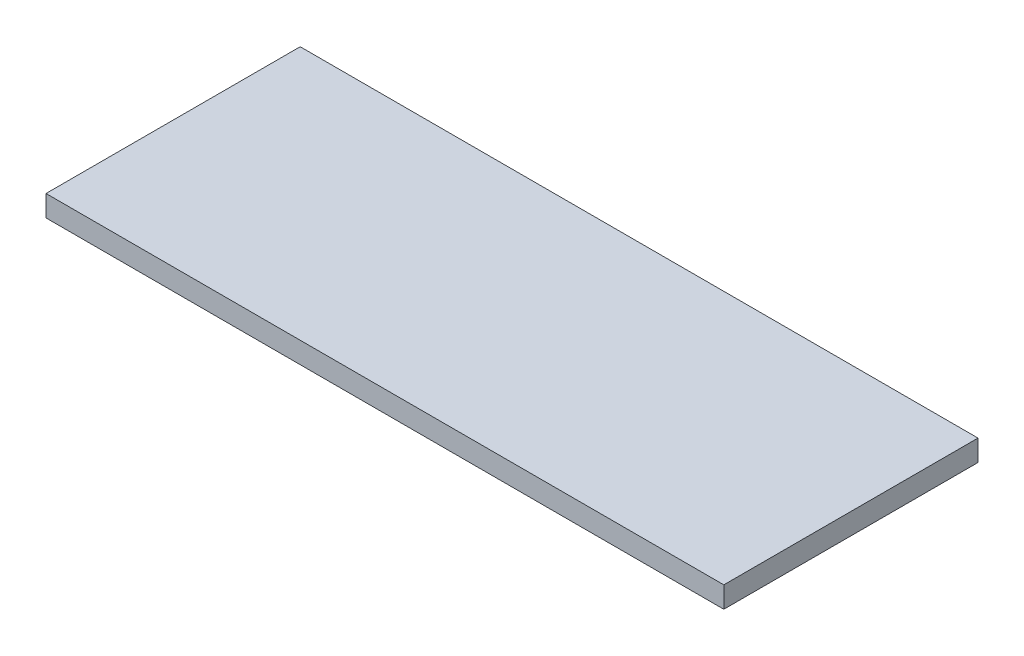
SolidWorks part; units mm, degrees
ref_plane "Front Plane" through (0, 0, 0) normal (0, 0, 1) x (1, 0, 0)
ref_plane "Top Plane" through (0, 0, 0) normal (0, 1, 0) x (1, 0, 0)
ref_plane "Right Plane" through (0, 0, 0) normal (1, 0, 0) x (0, 0, -1)
sketch "Sketch1" plane through (0, 0, 0) normal (0, 1, 0) x (1, 0, 0)
  line L1 (-80, -30) -> (80, -30)
  line L2 (-80, -30) -> (-80, 30)
  line L3 (-80, 30) -> (80, 30)
  line L4 (80, -30) -> (80, 30)
  line L5 (-80, -30) -> (80, 30) construction
  line L6 (-80, 30) -> (80, -30) construction
  point P0 (0, 0)
  dimension "D1" = 160
  dimension "D2" = 60
extrude "Boss-Extrude1" add sketch "Sketch1" along normal blind 5
